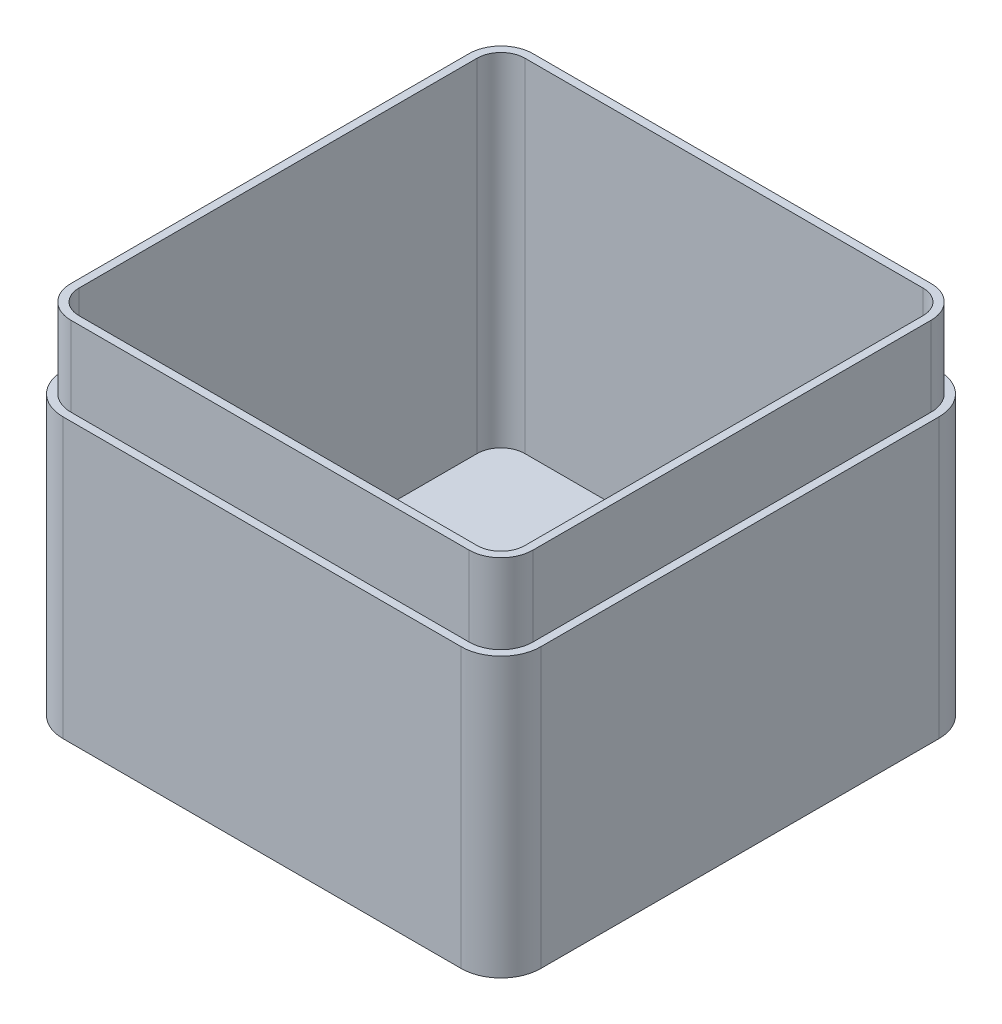
SolidWorks part; units mm, degrees
ref_plane "Front Plane" through (0, 0, 0) normal (0, 0, 1) x (1, 0, 0)
ref_plane "Top Plane" through (0, 0, 0) normal (0, 1, 0) x (1, 0, 0)
ref_plane "Right Plane" through (0, 0, 0) normal (1, 0, 0) x (0, 0, -1)
sketch "Sketch1" plane through (0, 0, 0) normal (0, 1, 0) x (1, 0, 0)
  line L1 (-60, -60) -> (60, -60)
  line L2 (-60, -60) -> (-60, 60)
  line L3 (-60, 60) -> (60, 60)
  line L4 (60, -60) -> (60, 60)
  line L5 (-60, -60) -> (60, 60) construction
  line L6 (-60, 60) -> (60, -60) construction
  point P0 (0, 0)
  dimension "D1" = 120
  dimension "D2" = 120
extrude "Boss-Extrude1" add sketch "Sketch1" along normal blind 90
fillet "Fillet1" radius 10 4 edges at (60, 45, -60) (-60, 45, -60) (60, 45, 60) (-60, 45, 60)
shell "Shell1" thickness 4
sketch "Sketch2" plane through (0, 90, 0) normal (0, 1, 0) x (1, 0, 0)
  line L4 (60, -50) -> (60, 50)
  line L5 (50, 60) -> (-50, 60)
  line L6 (-60, 50) -> (-60, -50)
  line L7 (-50, -60) -> (50, -60)
  line L8 (60, -50) -> (60, 50)
  line L9 (50, 60) -> (-50, 60)
  line L10 (-60, 50) -> (-60, -50)
  line L11 (-50, -60) -> (50, -60)
  arc A4 (60, 50) -> (50, 60) centre (50, 50) ccw
  arc A5 (-50, 60) -> (-60, 50) centre (-50, 50) ccw
  arc A6 (-60, -50) -> (-50, -60) centre (-50, -50) ccw
  arc A7 (50, -60) -> (60, -50) centre (50, -50) ccw
  arc A8 (60, 50) -> (50, 60) centre (50, 50) ccw
  arc A9 (-50, 60) -> (-60, 50) centre (-50, 50) ccw
  arc A10 (-60, -50) -> (-50, -60) centre (-50, -50) ccw
  arc A11 (50, -60) -> (60, -50) centre (50, -50) ccw
  dimension "D1" = 0
sketch "Sketch3" plane through (0, 90, 0) normal (0, 1, 0) x (1, 0, 0)
  line L8 (-50, -50) -> (50, -50)
  line L9 (-50, 50) -> (-50, -50)
  line L10 (50, 50) -> (-50, 50)
  line L11 (50, -50) -> (50, 50)
  line L12 (-50, -50) -> (50, -50)
  line L13 (-50, 50) -> (-50, -50)
  line L14 (50, 50) -> (-50, 50)
  line L15 (50, -50) -> (50, 50)
  line L20 (-50, -58) -> (50, -58)
  line L21 (-58, 50) -> (-58, -50)
  line L22 (50, 58) -> (-50, 58)
  line L23 (58, -50) -> (58, 50)
  line L24 (-50, -58) -> (50, -58)
  line L25 (-58, 50) -> (-58, -50)
  line L26 (50, 58) -> (-50, 58)
  line L27 (58, -50) -> (58, 50)
  arc A0 (-50, 60) -> (-60, 50) centre (-50, 50) ccw construction
  arc A1 (-50, 60) -> (-60, 50) centre (-50, 50) ccw
  arc A14 (-58, -50) -> (-50, -58) centre (-50, -50) ccw
  arc A15 (-50, 58) -> (-58, 50) centre (-50, 50) ccw
  arc A16 (58, 50) -> (50, 58) centre (50, 50) ccw
  arc A17 (50, -58) -> (58, -50) centre (50, -50) ccw
  arc A18 (-58, -50) -> (-50, -58) centre (-50, -50) ccw
  arc A19 (-50, 58) -> (-58, 50) centre (-50, 50) ccw
  arc A20 (58, 50) -> (50, 58) centre (50, 50) ccw
  arc A21 (50, -58) -> (58, -50) centre (50, -50) ccw
  line M22 (60, -50) -> (60, 50)
  arc M23 (60, 50) -> (50, 60) centre (50, 50) ccw
  line M24 (50, 60) -> (-50, 60)
  arc M25 (-50, 60) -> (-60, 50) centre (-50, 50) ccw
  line M26 (-60, 50) -> (-60, -50)
  arc M27 (-60, -50) -> (-50, -60) centre (-50, -50) ccw
  line M28 (-50, -60) -> (50, -60)
  arc M29 (50, -60) -> (60, -50) centre (50, -50) ccw
  dimension "D1" = 10
  dimension "D2" = 2
extrude "Cut-Extrude1" cut sketch "Sketch3" against normal blind 20 contours A21 L24 A18 L25 A19 L26 A20 L27 M29 M22 M23 M24 M25 M26 M27 M28
